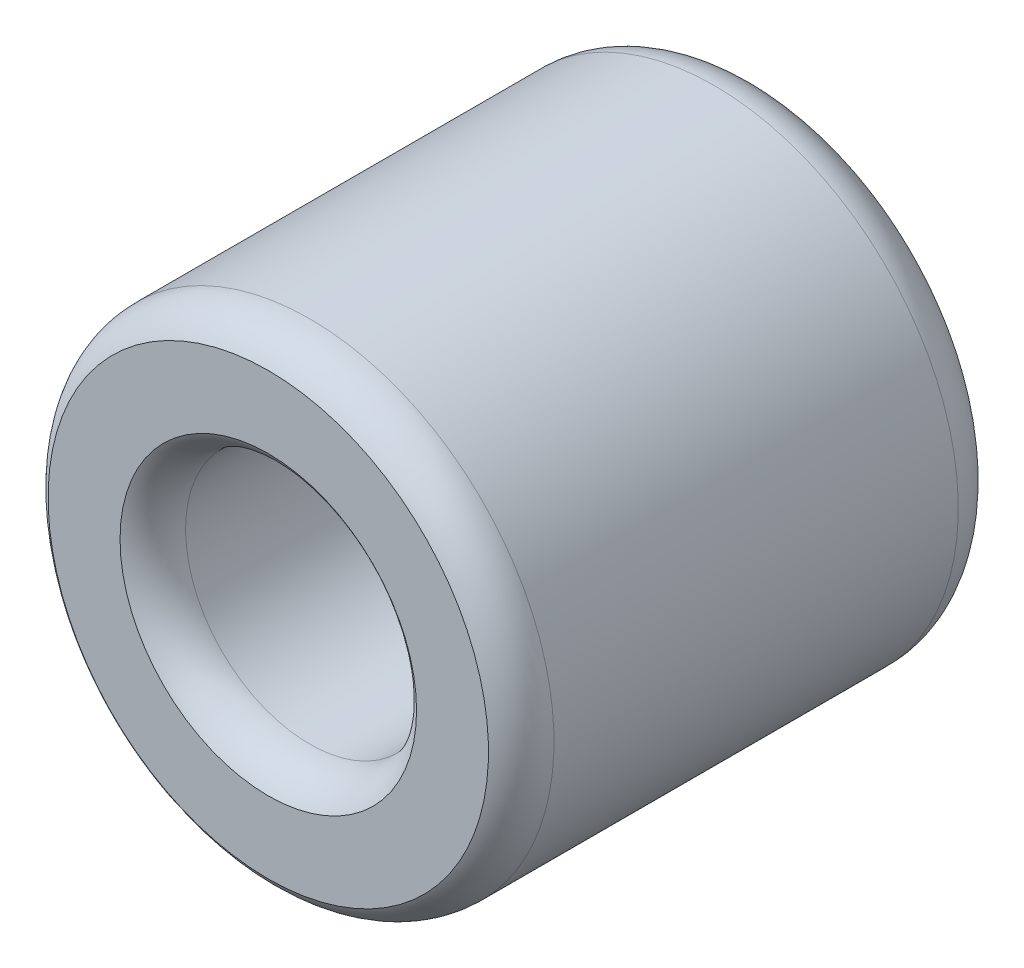
SolidWorks part; units mm, degrees
ref_plane "Front Plane" through (0, 0, 0) normal (0, 0, 1) x (1, 0, 0)
ref_plane "Top Plane" through (0, 0, 0) normal (0, 1, 0) x (1, 0, 0)
ref_plane "Right Plane" through (0, 0, 0) normal (1, 0, 0) x (0, 0, -1)
sketch "Sketch1" plane through (0, 0, 0) normal (0, 0, 1) x (1, 0, 0)
  line L0 (-1.6193, 0) -> (1.6193, 0) construction
  line L1 (-3.1813, 0) -> (3.1813, 0) construction
  point P4 (0, 0)
  point P8 (0, 0)
  point P9 (-1.6193, 0)
  point P10 (1.6193, 0)
  point P11 (3.1813, 0)
  point P12 (-3.1813, 0)
  dimension "ID" = 3.2385
  dimension "OD" = 6.3627
sketch "Sketch2" plane through (0, 0, 0) normal (1, 0, 0) x (0, 0, -1)
  line L0 (0, 3.1813) -> (0, -3.1813) construction
  line L1 (-3.175, 3.1813) -> (3.175, 3.1814) construction
  point P4 (0, 0)
  point P7 (0, 3.1813)
  point P9 (-3.175, 3.1813)
  point P10 (3.175, 3.1814)
  dimension "D1" = 6.3627
  dimension "Length" = 6.35
sketch "Sketch3" plane through (0, 0, 0) normal (0, 0, 1) x (1, 0, 0)
  circle A0 centre (0, 0) radius 1.6193
  circle A1 centre (0, 0) radius 3.1813
extrude "Boss-Extrude1" add sketch "Sketch3" along normal mid plane 6.35
sketch "Sketch4" plane through (0, 0, 0) normal (1, 0, 0) x (0, 0, -1)
  line L0 (3.175, 0) -> (-3.175, 0) construction
  line L1 (-3.175, 1.6192) -> (-3.175, -1.6193) construction
  line L2 (0, 3.1813) -> (0, -3.1813) construction
  line L3 (-3.175, -3.1813) -> (3.175, -3.1813) construction
  line L4 (-3.175, 1.6192) -> (3.175, 1.6193) construction
  line L5 (-3.175, 3.1813) -> (3.175, 3.1814) construction
  line L6 (-3.175, 3.1813) -> (-3.175, -3.1813) construction
  line L7 (-3.175, 3.1813) -> (3.175, 3.1813) construction
  line L8 (-2.6339, 3.1813) -> (-2.6339, 1.6192) construction
  line L9 (-2.6339, 3.1813) -> (-3.175, 3.1813)
  line L10 (-3.175, 3.1813) -> (-3.175, 2.8689)
  line L11 (-2.6339, 1.6192) -> (-3.175, 1.6192)
  line L12 (-3.175, 1.6192) -> (-3.175, 1.9317)
  line L13 (-3.175, 2.8689) -> (-3.8965, 1.6192) construction
  line L14 (3.175, 1.6193) -> (3.175, 1.9317)
  line L15 (2.6339, 1.6192) -> (3.175, 1.6193)
  line L16 (3.175, 3.1813) -> (3.175, 2.8689)
  line L17 (2.6339, 3.1813) -> (3.175, 3.1813)
  arc A0 (-2.6339, 3.1813) -> (-3.175, 2.8689) centre (-2.6339, 2.5565) ccw
  arc A1 (-2.6339, 1.6192) -> (-3.175, 1.9317) centre (-2.6339, 2.2441) cw
  arc A2 (2.6339, 1.6192) -> (3.175, 1.9317) centre (2.6339, 2.2441) ccw
  arc A3 (2.6339, 3.1813) -> (3.175, 2.8689) centre (2.6339, 2.5565) cw
  point P4 (0, 0)
  point P7 (-3.175, 0)
  dimension "D1" = 3.2385
  dimension "D2" = 6.35
  dimension "D3" = 0.3124
  dimension "D4" = 30
revolve "Cut-Revolve1" cut sketch "Sketch4" angle 360 about L0
equation "\"D1@Sketch2\"=\"OD@sketch1\""
equation "\"D1@Boss-Extrude1\"=\"Length@sketch2\""
equation "\"D1@Sketch4\"=\"ID@sketch1\""
equation "\"D2@Sketch4\"=\"Length@sketch2\""
equation "\"D3@Sketch4\"=((\"OD@sketch1\"-\"ID@sketch1\")/2)*.2"
